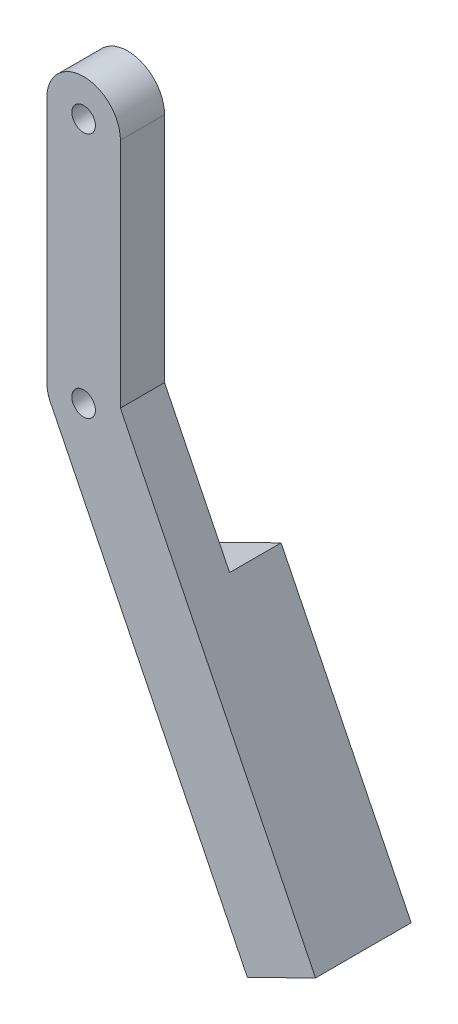
SolidWorks part; units mm, degrees
ref_plane "Alzado" through (0, 0, 0) normal (0, 0, 1) x (1, 0, 0)
ref_plane "Planta" through (0, 0, 0) normal (0, 1, 0) x (1, 0, 0)
ref_plane "Vista lateral" through (0, 0, 0) normal (1, 0, 0) x (0, 0, -1)
sketch "Croquis1" plane through (0, 0, 0) normal (0, 0, 1) x (1, 0, 0)
  line L0 (0, 0) -> (0, 33.48) construction
  line L1 (5, 1.95) -> (-4.2625, -2.6137) construction
  line L3 (-5, 33.48) -> (-5, 0)
  line L5 (5, 33.48) -> (5, 0)
  line L6 (5, 1.95) -> (31.5185, -51.8716)
  line L7 (-4.2625, -2.6137) -> (22.2561, -56.4353)
  line L8 (31.5185, -51.8716) -> (22.2561, -56.4353)
  arc A0 (5, 33.48) -> (-5, 33.48) centre (0, 33.48) ccw
  arc A1 (-5, 0) -> (5, 0) centre (0, 0) ccw
  point P12 (0, 38.48)
  dimension "D1" = 33.48
  dimension "D2" = 10
  dimension "D3" = 153.77
  dimension "D4" = 1.95
  dimension "D5" = 60
extrude "Saliente-Extruir1" add sketch "Croquis1" along normal blind 6 contours L3 A1 L5 A0 | A1 L7 L8 L6 L5
sketch "Croquis2" plane through (0, 0, 6) normal (0, 0, 1) x (1, 0, 0)
  circle A0 centre (0, 33.48) radius 1.6
  circle A1 centre (0, 0) radius 1.6
  dimension "D1" = 3.2
  dimension "D2" = 3.2
extrude "Cortar-Extruir1" cut sketch "Croquis2" against normal through all
sketch "Croquis3" plane through (0, 0, 0) normal (0, 0, -1) x (-1, 0, 0)
  line L0 (-31.5185, -51.8716) -> (-22.2561, -56.4353)
  line L1 (-31.5185, -51.8716) -> (-13.8395, -15.9905)
  line L2 (-22.2561, -56.4353) -> (-4.5771, -20.5543)
  line L3 (-13.8395, -15.9905) -> (-4.5771, -20.5543)
  dimension "D1" = 40
extrude "Saliente-Extruir2" add sketch "Croquis3" along normal blind 7
